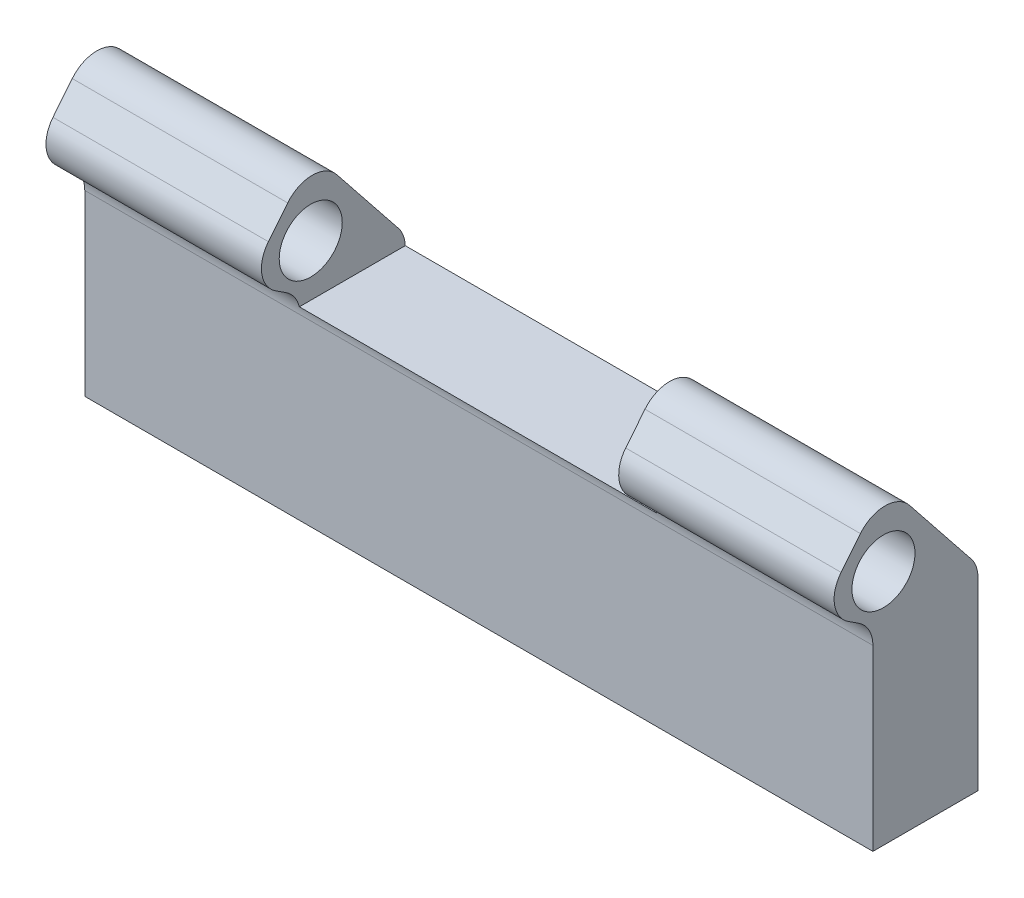
SolidWorks part; units mm, degrees
ref_plane "Alzado" through (0, 0, 0) normal (0, 0, 1) x (1, 0, 0)
ref_plane "Planta" through (0, 0, 0) normal (0, 1, 0) x (1, 0, 0)
ref_plane "Vista lateral" through (0, 0, 0) normal (1, 0, 0) x (0, 0, -1)
sketch "Croquis1" plane through (0, 0, 0) normal (0, 1, 0) x (1, 0, 0)
  line L1 (-37.5, 5) -> (37.5, 5)
  line L2 (-37.5, 5) -> (-37.5, -5)
  line L3 (-37.5, -5) -> (37.5, -5)
  line L4 (37.5, 5) -> (37.5, -5)
  line L5 (-37.5, 5) -> (37.5, -5) construction
  line L6 (-37.5, -5) -> (37.5, 5) construction
  point P0 (0, 0)
  dimension "D1" = 75
  dimension "D2" = 10
extrude "Saliente-Extruir1" add sketch "Croquis1" along normal blind 15
sketch "Croquis2" plane through (-37.5, 0, 0) normal (-1, 0, 0) x (0, 0, 1)
  line L0 (-5, 15) -> (5, 15)
  line L2 (8.0264, 24.5099) -> (6.1895, 26.7858)
  line L4 (5, 15) -> (5, 16.9742)
  line L5 (6.3731, 19.4947) -> (7.3188, 20.1051)
  line L6 (-5, 15) -> (-5, 17.5588)
  line L7 (-4.3456, 19.4292) -> (1.5094, 26.7719)
  arc A0 (1.5094, 26.7719) -> (6.1895, 26.7858) centre (3.855, 24.9016) cw
  arc A1 (7.3188, 20.1051) -> (8.0264, 24.5099) centre (5.6919, 22.6257) ccw
  arc A2 (-5, 17.5588) -> (-4.3456, 19.4292) centre (-2, 17.5588) cw
  arc A3 (5, 16.9742) -> (6.3731, 19.4947) centre (8, 16.9742) cw
  point P11 (3.8408, 29.6957)
  point P14 (10.1214, 21.9141)
  dimension "D1" = 10
extrude "Saliente-Extruir2" add sketch "Croquis2" against normal up to surface (75 mm away) up to face at (37.5, 7.5, 0)
sketch "Croquis3" plane through (0, 0, -5) normal (0, 0, -1) x (-1, 0, 0)
  line L0 (0, 0) -> (0, 27.9016) construction
  line L1 (37.5, 27.9016) -> (-37.5, 27.9016) construction
  line L3 (17, 17.6699) -> (-17, 17.6699)
  line L4 (17, 17.6699) -> (17, 38.1332)
  line L5 (17, 38.1332) -> (-17, 38.1332)
  line L6 (-17, 17.6699) -> (-17, 38.1332)
  line L7 (17, 17.6699) -> (-17, 38.1332) construction
  line L8 (17, 38.1332) -> (-17, 17.6699) construction
  dimension "D1" = 34
extrude "Cortar-Extruir1" cut sketch "Croquis3" against normal blind 53
sketch "Croquis4" plane through (37.5, 0, 0) normal (1, 0, 0) x (0, 0, -1)
  circle A0 centre (-3.9967, 22.5846) radius 3
  dimension "D1" = 6
extrude "Cortar-Extruir2" cut sketch "Croquis4" against normal blind 82
sketch "Croquis5" plane through (0, 0, 0) normal (0, -1, 0) x (1, 0, 0)
  circle A0 centre (0, 0) radius 3
  circle A1 centre (25, 0) radius 3
  circle A2 centre (-25, 0) radius 3
  dimension "D1" = 6
  dimension "D2" = 6
  dimension "D3" = 6
  dimension "D4" = 25
  dimension "D5" = 25
extrude "Cortar-Extruir3" cut sketch "Croquis5" against normal blind 6
